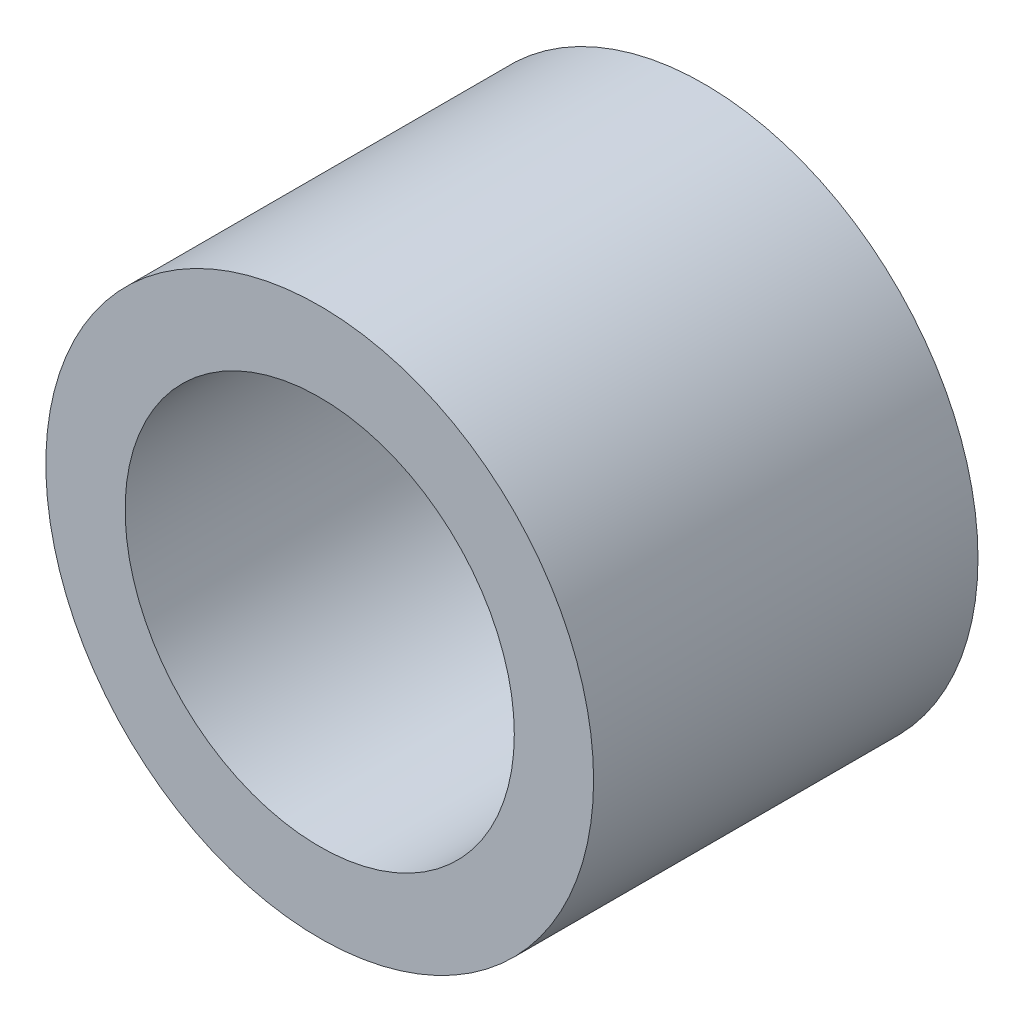
SolidWorks part; units mm, degrees
ref_plane "Front Plane" through (0, 0, 0) normal (0, 0, 1) x (1, 0, 0)
ref_plane "Top Plane" through (0, 0, 0) normal (0, 1, 0) x (1, 0, 0)
ref_plane "Right Plane" through (0, 0, 0) normal (1, 0, 0) x (0, 0, -1)
sketch "S01 - Installed brass envelope - simplified threads" plane through (0, 0, 0) normal (0, 0, 1) x (1, 0, 0)
  circle A0 centre (0, 0) radius 2.85
  circle A1 centre (0, 0) radius 2.025
extrude "01 - Installed brass envelope - simplified threads" add sketch "S01 - Installed brass envelope - simplified threads" along normal blind 4
